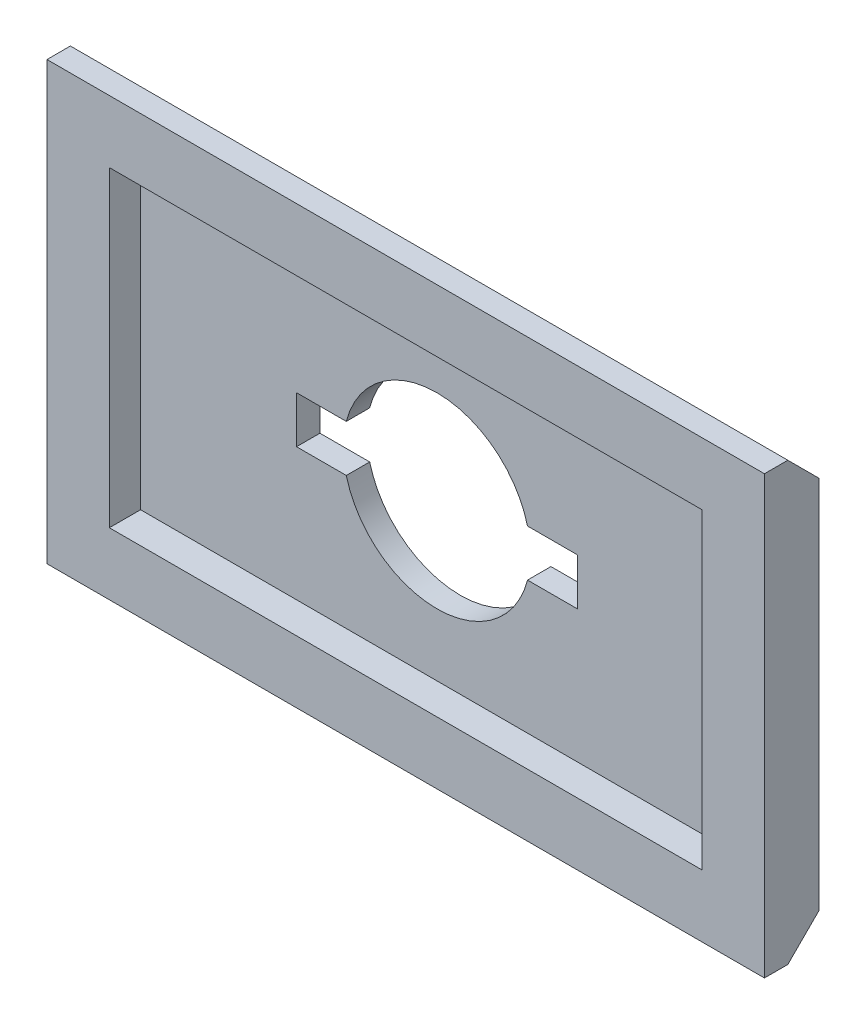
SolidWorks part; units mm, degrees
ref_plane "前视基准面" through (0, 0, 0) normal (0, 0, 1) x (1, 0, 0)
ref_plane "上视基准面" through (0, 0, 0) normal (0, 1, 0) x (1, 0, 0)
ref_plane "右视基准面" through (0, 0, 0) normal (1, 0, 0) x (0, 0, -1)
other "Configuration Table"
sketch "草图1" plane through (0, 0, 0) normal (0, 0, 1) x (1, 0, 0)
  line L0 (-16.7174, 0) -> (18.4672, 0) construction
  line L1 (-23, -14) -> (23, -14)
  line L2 (-23, -14) -> (-23, 14)
  line L3 (-23, 14) -> (23, 14)
  line L4 (23, -14) -> (23, 14)
  line L5 (-23, -14) -> (23, 14) construction
  line L6 (-23, 14) -> (23, -14) construction
  line L7 (0, 11.759) -> (0, -11.5047) construction
  line L8 (5.8095, 1.5) -> (9, 1.5)
  line L9 (-9, -1.5) -> (-5.8095, -1.5)
  line L10 (-9, -1.5) -> (-9, 1.5)
  line L11 (-9, 1.5) -> (-5.8095, 1.5)
  line L12 (9, -1.5) -> (9, 1.5)
  line L13 (5.8095, -1.5) -> (9, -1.5)
  arc A1 (5.8095, 1.5) -> (-5.8095, 1.5) centre (0, 0) ccw
  arc A2 (-5.8095, -1.5) -> (5.8095, -1.5) centre (0, 0) ccw
  dimension "D1" = 6
  dimension "D2" = 3
  dimension "D3" = 18
  dimension "D4" = 46
  dimension "D5" = 28
extrude "凸台-拉伸1" add sketch "草图1" along normal blind 3.5
sketch "草图2" plane through (0, 0, 3.5) normal (0, 0, 1) x (1, 0, 0)
  line L8 (19, -10) -> (19, 10)
  line L9 (19, 10) -> (-19, 10)
  line L10 (-19, 10) -> (-19, -10)
  line L11 (-19, -10) -> (19, -10)
  line L12 (19, -10) -> (19, 10)
  line L13 (19, 10) -> (-19, 10)
  line L14 (-19, 10) -> (-19, -10)
  line L15 (-19, -10) -> (19, -10)
  dimension "D1" = 4
extrude "切除-拉伸1" cut sketch "草图2" against normal blind 2
chamfer "倒角1" distance 2 angle 45 2 edges at (0, 14, 0) (0, -14, 0)
